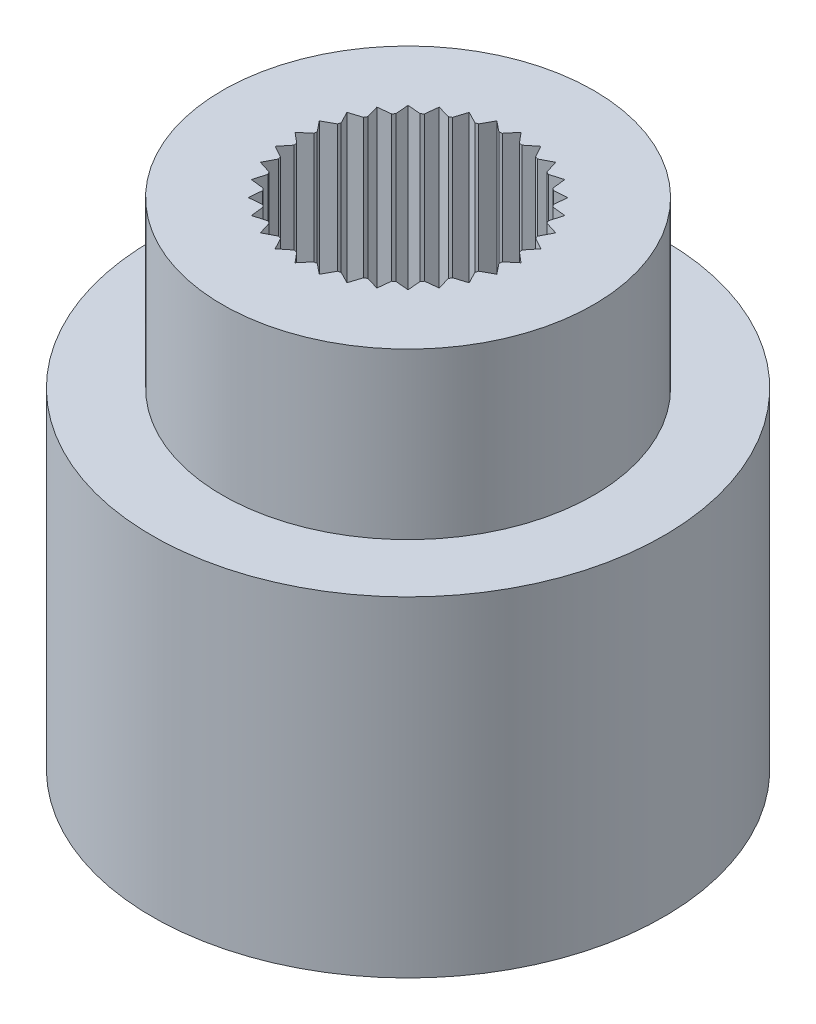
SolidWorks part; units mm, degrees
ref_plane "Front Plane" through (0, 0, 0) normal (0, 0, 1) x (1, 0, 0)
ref_plane "Top Plane" through (0, 0, 0) normal (0, 1, 0) x (1, 0, 0)
ref_plane "Right Plane" through (0, 0, 0) normal (1, 0, 0) x (0, 0, -1)
sketch "Sketch1" plane through (0, 0, 0) normal (1, 0, 0) x (0, 0, -1)
  line L0 (0, 0) -> (0, 27.9576) construction
  line L1 (-6.2, 0) -> (-6.2, 8)
  line L2 (-6.2, 8) -> (-4.5, 8)
  line L3 (-4.5, 8) -> (-4.5, 12)
  line L4 (-4.5, 12) -> (-2.5, 12)
  line L5 (-2.5, 12) -> (-2.5, 6)
  line L6 (-2.5, 6) -> (-4.2, 6)
  line L7 (-4.2, 6) -> (-4.2, 0)
  line L8 (-4.2, 0) -> (-6.2, 0)
  dimension "D1" = 2.5
  dimension "D2" = 4.2
  dimension "D3" = 2
  dimension "D4" = 2
  dimension "D5" = 12
  dimension "D6" = 6
  dimension "D7" = 4
revolve "Revolve1" add sketch "Sketch1" angle 360 about L0
sketch "Sketch2" plane through (0, 0, 0) normal (0, -1, 0) x (1, 0, 0)
  line L0 (0, 0) -> (0, 6.2) construction
  line L1 (-0.2329, 4.1478) -> (0, 4.4254)
  line L2 (0.2329, 4.1478) -> (0, 4.4254)
  line L3 (0, 4.4254) -> (0.2571, 4.119)
  line L4 (0.2329, 4.1478) -> (0.4955, 4.3976)
  line L5 (0.6959, 4.0956) -> (0.4955, 4.3976)
  line L6 (0.6959, 4.0956) -> (0.9847, 4.3144)
  line L7 (1.1501, 3.992) -> (0.9847, 4.3144)
  line L8 (1.1501, 3.992) -> (1.4616, 4.177)
  line L9 (1.5898, 3.8381) -> (1.4616, 4.177)
  line L10 (1.5898, 3.8381) -> (1.9201, 3.9871)
  line L11 (2.0095, 3.636) -> (1.9201, 3.9871)
  line L12 (2.0095, 3.636) -> (2.3544, 3.7471)
  line L13 (2.404, 3.3881) -> (2.3544, 3.7471)
  line L14 (2.404, 3.3881) -> (2.7592, 3.4599)
  line L15 (2.7682, 3.0976) -> (2.7592, 3.4599)
  line L16 (2.7682, 3.0976) -> (3.1292, 3.1292)
  line L17 (3.0976, 2.7682) -> (3.1292, 3.1292)
  line L18 (3.0976, 2.7682) -> (3.4599, 2.7592)
  line L19 (3.3881, 2.404) -> (3.4599, 2.7592)
  line L20 (3.3881, 2.404) -> (3.7471, 2.3544)
  line L21 (3.636, 2.0095) -> (3.7471, 2.3544)
  line L22 (3.636, 2.0095) -> (3.9871, 1.9201)
  line L23 (3.8381, 1.5898) -> (3.9871, 1.9201)
  line L24 (3.8381, 1.5898) -> (4.177, 1.4616)
  line L25 (3.992, 1.1501) -> (4.177, 1.4616)
  line L26 (3.992, 1.1501) -> (4.3144, 0.9847)
  line L27 (4.0956, 0.6959) -> (4.3144, 0.9847)
  line L28 (4.0956, 0.6959) -> (4.3976, 0.4955)
  line L29 (4.1478, 0.2329) -> (4.3976, 0.4955)
  line L30 (4.1478, 0.2329) -> (4.4254, 0)
  line L31 (4.1478, -0.2329) -> (4.4254, 0)
  line L32 (4.1478, -0.2329) -> (4.3976, -0.4955)
  line L33 (4.0956, -0.6959) -> (4.3976, -0.4955)
  line L34 (4.0956, -0.6959) -> (4.3144, -0.9847)
  line L35 (3.992, -1.1501) -> (4.3144, -0.9847)
  line L36 (3.992, -1.1501) -> (4.177, -1.4616)
  line L37 (3.8381, -1.5898) -> (4.177, -1.4616)
  line L38 (3.8381, -1.5898) -> (3.9871, -1.9201)
  line L39 (3.636, -2.0095) -> (3.9871, -1.9201)
  line L40 (3.636, -2.0095) -> (3.7471, -2.3544)
  line L41 (3.3881, -2.404) -> (3.7471, -2.3544)
  line L42 (3.3881, -2.404) -> (3.4599, -2.7592)
  line L43 (3.0976, -2.7682) -> (3.4599, -2.7592)
  line L44 (3.0976, -2.7682) -> (3.1292, -3.1292)
  line L45 (2.7682, -3.0976) -> (3.1292, -3.1292)
  line L46 (2.7682, -3.0976) -> (2.7592, -3.4599)
  line L47 (2.404, -3.3881) -> (2.7592, -3.4599)
  line L48 (2.404, -3.3881) -> (2.3544, -3.7471)
  line L49 (2.0095, -3.636) -> (2.3544, -3.7471)
  line L50 (2.0095, -3.636) -> (1.9201, -3.9871)
  line L51 (1.5898, -3.8381) -> (1.9201, -3.9871)
  line L52 (1.5898, -3.8381) -> (1.4616, -4.177)
  line L53 (1.1501, -3.992) -> (1.4616, -4.177)
  line L54 (1.1501, -3.992) -> (0.9847, -4.3144)
  line L55 (0.6959, -4.0956) -> (0.9847, -4.3144)
  line L56 (0.6959, -4.0956) -> (0.4955, -4.3976)
  line L57 (0.2329, -4.1478) -> (0.4955, -4.3976)
  line L58 (0.2329, -4.1478) -> (0, -4.4254)
  line L59 (-0.2329, -4.1478) -> (0, -4.4254)
  line L60 (-0.2329, -4.1478) -> (-0.4955, -4.3976)
  line L61 (-0.6959, -4.0956) -> (-0.4955, -4.3976)
  line L62 (-0.6959, -4.0956) -> (-0.9847, -4.3144)
  line L63 (-1.1501, -3.992) -> (-0.9847, -4.3144)
  line L64 (-1.1501, -3.992) -> (-1.4616, -4.177)
  line L65 (-1.5898, -3.8381) -> (-1.4616, -4.177)
  line L66 (-1.5898, -3.8381) -> (-1.9201, -3.9871)
  line L67 (-2.0095, -3.636) -> (-1.9201, -3.9871)
  line L68 (-2.0095, -3.636) -> (-2.3544, -3.7471)
  line L69 (-2.404, -3.3881) -> (-2.3544, -3.7471)
  line L70 (-2.404, -3.3881) -> (-2.7592, -3.4599)
  line L71 (-2.7682, -3.0976) -> (-2.7592, -3.4599)
  line L72 (-2.7682, -3.0976) -> (-3.1292, -3.1292)
  line L73 (-3.0976, -2.7682) -> (-3.1292, -3.1292)
  line L74 (-3.0976, -2.7682) -> (-3.4599, -2.7592)
  line L75 (-3.3881, -2.404) -> (-3.4599, -2.7592)
  line L76 (-3.3881, -2.404) -> (-3.7471, -2.3544)
  line L77 (-3.636, -2.0095) -> (-3.7471, -2.3544)
  line L78 (-3.636, -2.0095) -> (-3.9871, -1.9201)
  line L79 (-3.8381, -1.5898) -> (-3.9871, -1.9201)
  line L80 (-3.8381, -1.5898) -> (-4.177, -1.4616)
  line L81 (-3.992, -1.1501) -> (-4.177, -1.4616)
  line L82 (-3.992, -1.1501) -> (-4.3144, -0.9847)
  line L83 (-4.0956, -0.6959) -> (-4.3144, -0.9847)
  line L84 (-4.0956, -0.6959) -> (-4.3976, -0.4955)
  line L85 (-4.1478, -0.2329) -> (-4.3976, -0.4955)
  line L86 (-4.1478, -0.2329) -> (-4.4254, 0)
  line L87 (-4.1478, 0.2329) -> (-4.4254, 0)
  line L88 (-4.1478, 0.2329) -> (-4.3976, 0.4955)
  line L89 (-4.0956, 0.6959) -> (-4.3976, 0.4955)
  line L90 (-4.0956, 0.6959) -> (-4.3144, 0.9847)
  line L91 (-3.992, 1.1501) -> (-4.3144, 0.9847)
  line L92 (-3.992, 1.1501) -> (-4.177, 1.4616)
  line L93 (-3.8582, 1.5822) -> (-4.177, 1.4616)
  line L94 (-3.8469, 1.6094) -> (-3.9871, 1.9201)
  line L95 (-3.6568, 2.0042) -> (-3.9871, 1.9201)
  line L96 (-3.6425, 2.03) -> (-3.7471, 2.3544)
  line L97 (-3.4094, 2.401) -> (-3.7471, 2.3544)
  line L98 (-3.3924, 2.425) -> (-3.4599, 2.7592)
  line L99 (-3.1191, 2.7677) -> (-3.4599, 2.7592)
  line L100 (-3.0995, 2.7896) -> (-3.1292, 3.1292)
  line L101 (-2.7896, 3.0995) -> (-3.1292, 3.1292)
  line L102 (-2.7677, 3.1191) -> (-2.7592, 3.4599)
  line L103 (-2.425, 3.3924) -> (-2.7592, 3.4599)
  line L104 (-2.401, 3.4094) -> (-2.3544, 3.7471)
  line L105 (-2.0095, 3.636) -> (-2.3544, 3.7471)
  line L106 (-2.0095, 3.636) -> (-1.9201, 3.9871)
  line L107 (-1.6094, 3.8469) -> (-1.9201, 3.9871)
  line L108 (-1.5822, 3.8582) -> (-1.4616, 4.177)
  line L109 (-1.1501, 3.992) -> (-1.4616, 4.177)
  line L110 (-1.1501, 3.992) -> (-0.9847, 4.3144)
  line L111 (-0.6959, 4.0956) -> (-0.9847, 4.3144)
  line L112 (-0.6959, 4.0956) -> (-0.4955, 4.3976)
  line L113 (-0.2329, 4.1478) -> (-0.4955, 4.3976)
  circle A0 centre (0, 0) radius 6.2 construction
  arc A1 (-2.0042, 3.6568) -> (-2.03, 3.6425) centre (0, 0) ccw
  arc A2 (-3.3924, 2.425) -> (-3.4094, 2.401) centre (0, 0) ccw
  arc A3 (-3.6425, 2.03) -> (-3.6568, 2.0042) centre (0, 0) ccw
  arc A4 (-2.401, 3.4094) -> (-2.425, 3.3924) centre (0, 0) ccw
  arc A5 (-2.7677, 3.1191) -> (-2.7896, 3.0995) centre (0, 0) ccw
  arc A6 (-3.0995, 2.7896) -> (-3.1191, 2.7677) centre (0, 0) ccw
  arc A7 (-3.8469, 1.6094) -> (-3.8582, 1.5822) centre (0, 0) ccw
  arc A9 (-1.5822, 3.8582) -> (-1.6094, 3.8469) centre (0, 0) ccw
  point P177 (0, 0)
  dimension "D2" = 40
  dimension "D3" = 0.4
  dimension "D4" = 56
extrude "Cut-Extrude1" cut sketch "Sketch2" against normal blind 6 contours L1 L113 L112 L111 L110 L109 L108 A9 L107 L106 L105 L104 A4 L103 L102 A5 L101 L100 A6 L99 L98 A2 L97 L96 A3 L95 L94 A7 L93 L92 L91 L90 L89 L88 L87 L86 L85 L84 L83 L82 L81 L80 L79 L78 L77 L76 L75 L74 L73 L72 L71 L70 L69 L68 L67 L66 L65 L64 L63 L62 L61 L60 L59 L58 L57 L56 L55 L54 L53 L52 L51 L50 L49 L48 L47 L46 L45 L44 L43 L42 L41 L40 L39 L38 L37 L36 L35 L34 L33 L32 L31 L30 L29 L28 L27 L26 L25 L24 L23 L22 L21 L20 L19 L18 L17 L16 L15 L14 L13 L12 L11 L10 L9 L8 L7 L6 L5 L4 L2
sketch "Sketch3" plane through (0, 12, 0) normal (0, 1, 0) x (1, 0, 0)
  line L0 (0, 2.7389) -> (0, 3.2693) construction
  line L1 (0, 2.7389) -> (-0.2414, 2.4512)
  line L2 (0, 2.7389) -> (0.2414, 2.4512)
  line L3 (0.5343, 2.6862) -> (0.2414, 2.4512)
  line L4 (0.5343, 2.6862) -> (0.715, 2.357)
  line L5 (1.0481, 2.5304) -> (0.715, 2.357)
  line L6 (1.0481, 2.5304) -> (1.1611, 2.1722)
  line L7 (1.5216, 2.2773) -> (1.1611, 2.1722)
  line L8 (1.5216, 2.2773) -> (1.5625, 1.9039)
  line L9 (1.9367, 1.9367) -> (1.5625, 1.9039)
  line L10 (1.9367, 1.9367) -> (1.9039, 1.5625)
  line L11 (2.2773, 1.5216) -> (1.9039, 1.5625)
  line L12 (2.2773, 1.5216) -> (2.1722, 1.1611)
  line L13 (2.5304, 1.0481) -> (2.1722, 1.1611)
  line L14 (2.5304, 1.0481) -> (2.357, 0.715)
  line L15 (2.6862, 0.5343) -> (2.357, 0.715)
  line L16 (2.6862, 0.5343) -> (2.4512, 0.2414)
  line L17 (2.7389, 0) -> (2.4512, 0.2414)
  line L18 (2.7389, 0) -> (2.4512, -0.2414)
  line L19 (2.6862, -0.5343) -> (2.4512, -0.2414)
  line L20 (2.6862, -0.5343) -> (2.357, -0.715)
  line L21 (2.5304, -1.0481) -> (2.357, -0.715)
  line L22 (2.5304, -1.0481) -> (2.1722, -1.1611)
  line L23 (2.2773, -1.5216) -> (2.1722, -1.1611)
  line L24 (2.2773, -1.5216) -> (1.9039, -1.5625)
  line L25 (1.9367, -1.9367) -> (1.9039, -1.5625)
  line L26 (1.9367, -1.9367) -> (1.5625, -1.9039)
  line L27 (1.5216, -2.2773) -> (1.5625, -1.9039)
  line L28 (1.5216, -2.2773) -> (1.1611, -2.1722)
  line L29 (1.0481, -2.5304) -> (1.1611, -2.1722)
  line L30 (1.0481, -2.5304) -> (0.715, -2.357)
  line L31 (0.5343, -2.6862) -> (0.715, -2.357)
  line L32 (0.5343, -2.6862) -> (0.2414, -2.4512)
  line L33 (0, -2.7389) -> (0.2414, -2.4512)
  line L34 (0, -2.7389) -> (-0.2414, -2.4512)
  line L35 (-0.5343, -2.6862) -> (-0.2414, -2.4512)
  line L36 (-0.5343, -2.6862) -> (-0.715, -2.357)
  line L37 (-1.0481, -2.5304) -> (-0.715, -2.357)
  line L38 (-1.0481, -2.5304) -> (-1.1611, -2.1722)
  line L39 (-1.5216, -2.2773) -> (-1.1611, -2.1722)
  line L40 (-1.5216, -2.2773) -> (-1.5625, -1.9039)
  line L41 (-1.9367, -1.9367) -> (-1.5625, -1.9039)
  line L42 (-1.9367, -1.9367) -> (-1.9039, -1.5625)
  line L43 (-2.2773, -1.5216) -> (-1.9039, -1.5625)
  line L44 (-2.2773, -1.5216) -> (-2.1722, -1.1611)
  line L45 (-2.5304, -1.0481) -> (-2.1722, -1.1611)
  line L46 (-2.5304, -1.0481) -> (-2.357, -0.715)
  line L47 (-2.6862, -0.5343) -> (-2.357, -0.715)
  line L48 (-2.6862, -0.5343) -> (-2.4512, -0.2414)
  line L49 (-2.7389, 0) -> (-2.4512, -0.2414)
  line L50 (-2.7389, 0) -> (-2.4512, 0.2414)
  line L51 (-2.6862, 0.5343) -> (-2.4512, 0.2414)
  line L52 (-2.6862, 0.5343) -> (-2.357, 0.715)
  line L53 (-2.5304, 1.0481) -> (-2.357, 0.715)
  line L54 (-2.5304, 1.0481) -> (-2.1722, 1.1611)
  line L55 (-2.2773, 1.5216) -> (-2.1722, 1.1611)
  line L56 (-2.2773, 1.5216) -> (-1.9039, 1.5625)
  line L57 (-1.9367, 1.9367) -> (-1.9039, 1.5625)
  line L58 (-1.9367, 1.9367) -> (-1.5625, 1.9039)
  line L59 (-1.5216, 2.2773) -> (-1.5625, 1.9039)
  line L60 (-1.5216, 2.2773) -> (-1.1611, 2.1722)
  line L61 (-1.0481, 2.5304) -> (-1.1611, 2.1722)
  line L62 (-1.0481, 2.5304) -> (-0.715, 2.357)
  line L63 (-0.5343, 2.6862) -> (-0.715, 2.357)
  line L64 (-0.5343, 2.6862) -> (-0.2414, 2.4512)
  point P103 (0, 0)
  dimension "D2" = 40
  dimension "D3" = 40
  dimension "D5" = 32
extrude "Cut-Extrude2" cut sketch "Sketch3" against normal blind 6
